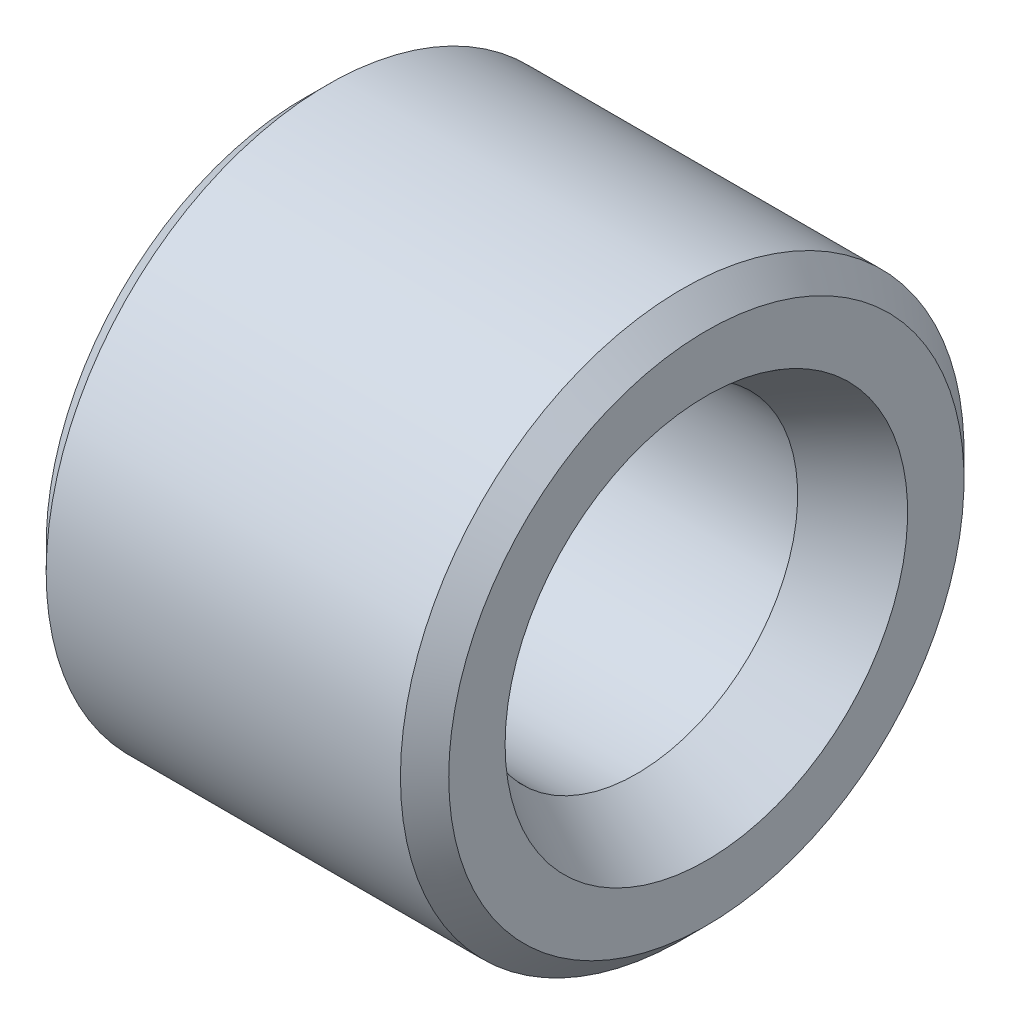
SolidWorks part; units mm, degrees
ref_plane "Front Plane" through (0, 0, 0) normal (0, 0, 1) x (1, 0, 0)
ref_plane "Top Plane" through (0, 0, 0) normal (0, 1, 0) x (1, 0, 0)
ref_plane "Right Plane" through (0, 0, 0) normal (1, 0, 0) x (0, 0, -1)
sketch "Sketch1" plane through (0, 0, 0) normal (0, 0, 1) x (1, 0, 0)
  line L0 (0, 0) -> (5, 0) construction
  line L1 (0, 2) -> (0, 3.5)
  line L2 (0, 3.5) -> (5, 3.5)
  line L4 (5, 3.5) -> (5, 2)
  line L6 (5, 2) -> (0, 2)
  dimension "L" = 5
  dimension "D_s" = 4
  dimension "D" = 7
  dimension "T" = 1.5
revolve "Revolve1" add sketch "Sketch1" angle 360 about L0
chamfer "Chamfer1" distance 0.3 2 edges at (5, 0, 3.5) (0, 0, 3.5)
sketch "Sketch2" plane through (0, 0, 0) normal (0, 0, 1) x (1, 0, 0)
  line L0 (0, 0) -> (5, 0) construction
  line L1 (0, 2.5) -> (0, 2)
  line L2 (0, 2) -> (0.866, 2)
  line L3 (0.866, 2) -> (0, 2.5)
  line L4 (4.134, 2) -> (5, 2.5)
  line L5 (0, 2) -> (0, 3.5) construction
  line L8 (5, 2) -> (4.134, 2)
  line L9 (5, 2.5) -> (5, 2)
  line L10 (5, 2) -> (0, 2) construction
  line L11 (5, 3.5) -> (5, 2) construction
  dimension "FIX_4" = 0.5
  dimension "FIX_5" = 30
revolve "Cut-Revolve1" cut sketch "Sketch2" angle 360 about L0
